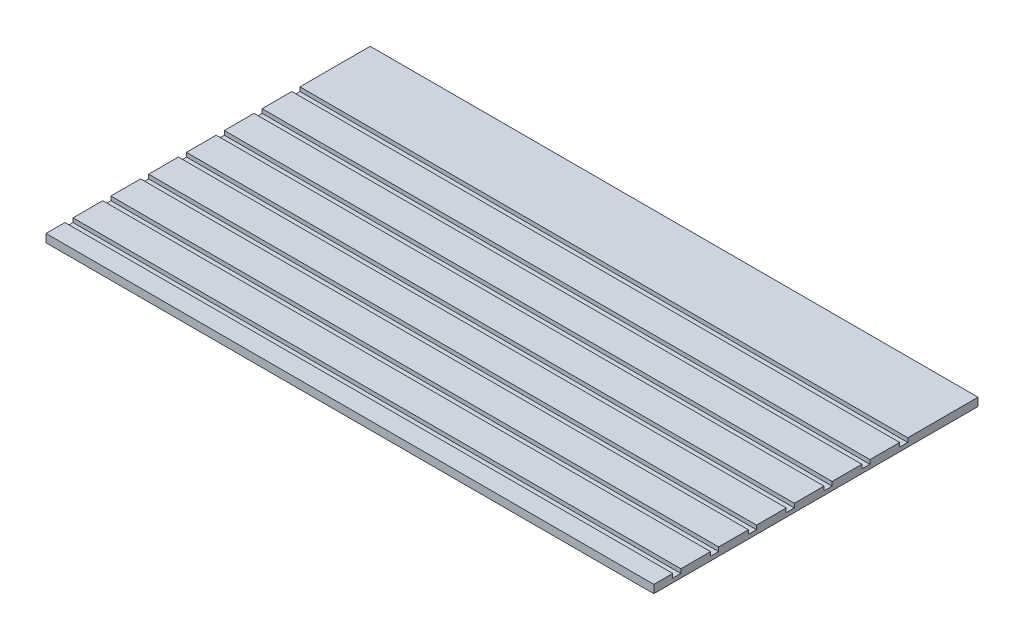
SolidWorks part; units mm, degrees
material "Maple"
ref_plane "Front Plane" through (0, 0, 0) normal (0, 0, 1) x (1, 0, 0)
ref_plane "Top Plane" through (0, 0, 0) normal (0, 1, 0) x (1, 0, 0)
ref_plane "Right Plane" through (0, 0, 0) normal (1, 0, 0) x (0, 0, -1)
sketch "Sketch1" plane through (0, 0, 0) normal (0, 1, 0) x (1, 0, 0)
  line L0 (-714.375, -381) -> (714.375, 381) construction
  line L1 (-714.375, -381) -> (714.375, -381)
  line L2 (-714.375, -381) -> (-714.375, 381)
  line L3 (-714.375, 381) -> (714.375, 381)
  line L4 (714.375, -381) -> (714.375, 381)
  dimension "D1" = 1428.75
  dimension "D2" = 762
extrude "Board" add sketch "Sketch1" along normal blind 19.05
sketch "Sketch4" plane through (-714.375, 0, 0) normal (-1, 0, 0) x (0, 0, 1)
  line L0 (-381, 19.05) -> (-381, 0) construction
  line L1 (-381, 19.05) -> (381, 19.05) construction
  line L2 (355.6, 19.05) -> (355.6, 9.525)
  line L3 (-357.4034, 19.05) -> (-338.3534, 19.05)
  line L4 (-357.4034, 19.05) -> (-357.4034, 9.525)
  line L5 (-357.4034, 9.525) -> (-338.3534, 9.525)
  line L6 (-338.3534, 19.05) -> (-338.3534, 9.525)
  line L7 (355.6, 19.05) -> (336.55, 19.05)
  line L8 (336.55, 19.05) -> (336.55, 9.525)
  line L9 (355.6, 9.525) -> (336.55, 9.525)
  line L11 (152.4, 19.05) -> (171.45, 19.05)
  line L12 (152.4, 19.05) -> (152.4, 9.525)
  line L13 (152.4, 9.525) -> (171.45, 9.525)
  line L14 (171.45, 19.05) -> (171.45, 9.525)
  line L15 (-196.85, 19.05) -> (-215.9, 19.05)
  line L16 (-196.85, 19.05) -> (-196.85, 9.525)
  line L17 (-196.85, 9.525) -> (-215.9, 9.525)
  line L18 (-12.7, 19.05) -> (-12.7, 9.525)
  line L19 (-215.9, 19.05) -> (-215.9, 9.525)
  line L23 (-12.7, 19.05) -> (-31.75, 19.05)
  line L24 (-31.75, 19.05) -> (-31.75, 9.525)
  line L25 (-12.7, 9.525) -> (-31.75, 9.525)
  dimension "D1" = 19.05
  dimension "D2" = 9.525
  dimension "D3" = 717.55
  dimension "D4" = 23.5966
  dimension "D5" = 165.1
  dimension "D6" = 165.1
  dimension "D7" = 165.1
extrude "X- Axis Grooves" [suppressed] cut sketch "Sketch4" against normal up to surface (1428.75 mm away)
sketch "Sketch5" plane through (0, 0, 381) normal (0, 0, 1) x (1, 0, 0)
  line L0 (-714.375, 19.05) -> (714.375, 19.05) construction
  line L1 (-695.325, 19.05) -> (-676.275, 19.05)
  line L2 (-695.325, 19.05) -> (-695.325, 9.525)
  line L3 (-695.325, 9.525) -> (-676.275, 9.525)
  line L4 (-676.275, 19.05) -> (-676.275, 9.525)
  line L5 (-714.375, 19.05) -> (-714.375, 0) construction
  line L6 (-346.075, 19.05) -> (-327.025, 19.05)
  line L7 (-346.075, 19.05) -> (-346.075, 9.525)
  line L8 (-346.075, 9.525) -> (-327.025, 9.525)
  line L9 (-327.025, 19.05) -> (-327.025, 9.525)
  line L22 (568.325, 19.05) -> (587.375, 19.05)
  line L23 (568.325, 19.05) -> (568.325, 9.525)
  line L24 (568.325, 9.525) -> (587.375, 9.525)
  line L25 (587.375, 19.05) -> (587.375, 9.525)
  dimension "D1" = 19.05
  dimension "D2" = 19.05
  dimension "D3" = 9.525
  dimension "D4" = 330.2
  dimension "D5" = 1244.6
extrude "Y-Axis Grooves" [suppressed] cut sketch "Sketch5" against normal up to surface (704.85 mm away)
sketch "Sketch6" plane through (0, 19.05, 0) normal (0, 1, 0) x (1, 0, 0)
  line L0 (-598.0647, 61.6513) -> (567.6073, 61.6513) construction
  text T0 "1'x1'\r\n" font "Century Gothic" height 76.2
extrude "\"1\"" [suppressed] cut sketch "Sketch6" against normal blind 1.27
sketch "Sketch7" plane through (0, 19.05, 0) normal (0, 1, 0) x (1, 0, 0)
  line L0 (-70.4936, -248.9336) -> (1439.7947, -248.9336) construction
  text T0 "2'x4'\r\n" font "Century Gothic" height 152.4
extrude "\"2'x4'\"" [suppressed] cut sketch "Sketch7" against normal blind 1.27
sketch "Sketch8" [suppressed] plane through (-714.375, 0, 0) normal (-1, 0, 0) x (0, 0, 1)
  line L1 (-389.1534, 19.05) -> (-370.1034, 19.05)
  line L2 (-389.1534, 19.05) -> (-389.1534, 9.525)
  line L3 (-389.1534, 9.525) -> (-370.1034, 9.525)
  line L4 (-370.1034, 19.05) -> (-370.1034, 9.525)
extrude "Boss-Extrude1" [suppressed] add sketch "Sketch8" against normal up to surface (1428.75 mm away)
sketch "Sketch9" plane through (-714.375, 0, 0) normal (-1, 0, 0) x (0, 0, 1)
  line L0 (-381, 19.05) -> (381, 19.05) construction
  line L1 (317.5, 19.05) -> (336.55, 19.05)
  line L2 (317.5, 19.05) -> (317.5, 9.525)
  line L3 (317.5, 9.525) -> (336.55, 9.525)
  line L4 (336.55, 19.05) -> (336.55, 9.525)
  line L5 (381, 19.05) -> (381, 0) construction
  dimension "D1" = 19.05
  dimension "D2" = 9.525
  dimension "D3" = 44.45
extrude "Cut-Extrude1" cut sketch "Sketch9" against normal through all
pattern_linear "LPattern1" count 7 spacing 88.9 along (0, 0, -1) of "Cut-Extrude1"
sketch "Sketch10" plane through (0, 19.05, 0) normal (0, 1, 0) x (1, 0, 0)
  line L0 (-714.375, 355.6) -> (714.375, 355.6)
  line L1 (-714.375, 196.85) -> (-714.375, 127) construction
  line L2 (714.375, 127) -> (714.375, 196.85) construction
  line L3 (-714.375, 171.45) -> (714.375, 171.45)
  line L4 (-714.375, 19.05) -> (-714.375, -50.8) construction
  line L5 (714.375, -50.8) -> (714.375, 19.05) construction
  line L6 (-714.375, -12.7) -> (714.375, -12.7)
  line L7 (-714.375, -69.85) -> (-714.375, -139.7) construction
  line L8 (714.375, -139.7) -> (714.375, -69.85) construction
  line L9 (-714.375, -196.85) -> (714.375, -196.85)
  line L10 (-714.375, -158.75) -> (-714.375, -228.6) construction
  line L11 (714.375, -228.6) -> (714.375, -158.75) construction
  line L12 (-714.375, -381) -> (714.375, -381) construction
  dimension "D1" = 184.15
  dimension "D2" = 184.15
  dimension "D3" = 184.15
  dimension "D4" = 184.15
split line "Split Line1" [suppressed]
